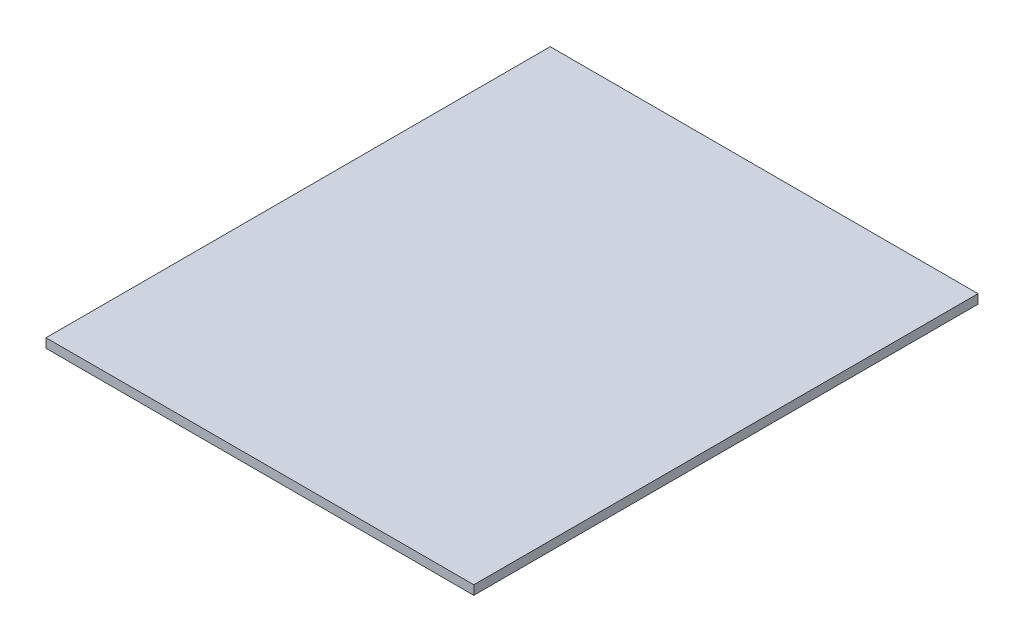
SolidWorks part; units mm, degrees
ref_plane "Front Plane" through (0, 0, 0) normal (0, 0, 1) x (1, 0, 0)
ref_plane "Top Plane" through (0, 0, 0) normal (0, 1, 0) x (1, 0, 0)
ref_plane "Right Plane" through (0, 0, 0) normal (1, 0, 0) x (0, 0, -1)
sketch "Sketch1" plane through (0, 0, 0) normal (0, 1, 0) x (1, 0, 0)
  line L1 (70, 82.5) -> (-70, 82.5)
  line L2 (70, 82.5) -> (70, -82.5)
  line L3 (70, -82.5) -> (-70, -82.5)
  line L4 (-70, 82.5) -> (-70, -82.5)
  line L5 (70, 82.5) -> (-70, -82.5) construction
  line L6 (70, -82.5) -> (-70, 82.5) construction
  point P0 (0, 0)
  dimension "D1" = 140
  dimension "D2" = 165
extrude "Boss-Extrude1" add sketch "Sketch1" along normal blind 3
